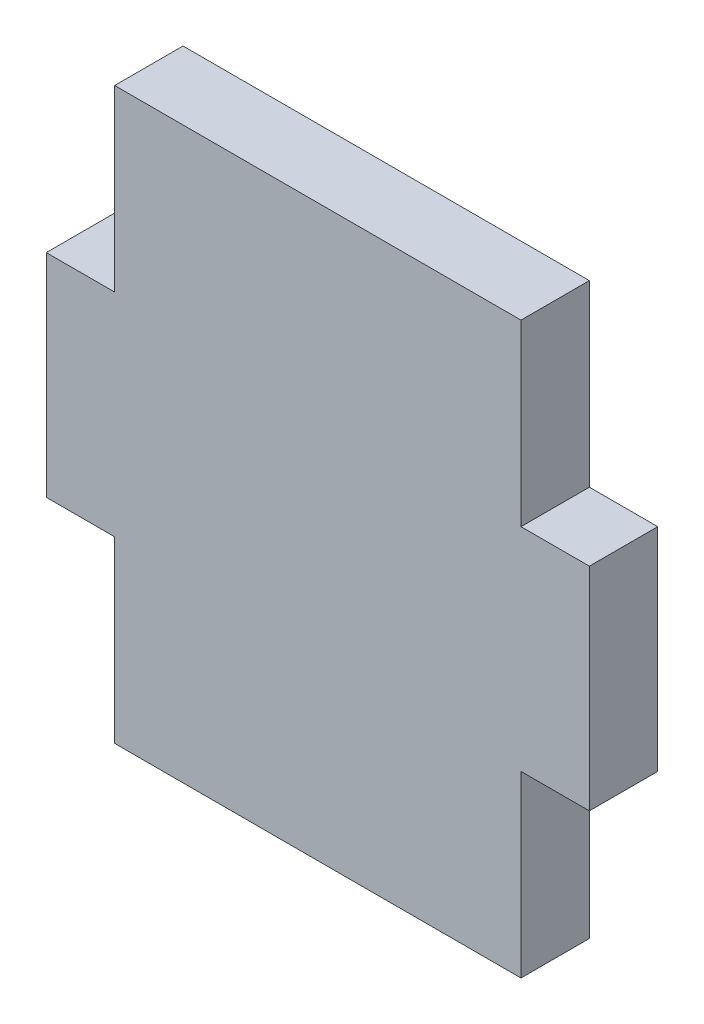
SolidWorks part; units mm, degrees
ref_plane "Front Plane" through (0, 0, 0) normal (0, 0, 1) x (1, 0, 0)
ref_plane "Top Plane" through (0, 0, 0) normal (0, 1, 0) x (1, 0, 0)
ref_plane "Right Plane" through (0, 0, 0) normal (1, 0, 0) x (0, 0, -1)
sketch "Sketch1" plane through (0, 0, 0) normal (0, 0, 1) x (1, 0, 0)
  line L0 (0, -14.224) -> (0, -10.2362)
  line L1 (0, -10.2362) -> (-1.524, -10.2362)
  line L2 (-1.524, -10.2362) -> (-1.524, -5.5118)
  line L3 (-1.524, -5.5118) -> (0, -5.5118)
  line L4 (0, -5.5118) -> (0, -1.524)
  line L5 (0, -1.524) -> (9.0572, -1.524)
  line L6 (9.0572, -1.524) -> (9.0572, -5.5118)
  line L7 (9.0572, -5.5118) -> (10.5812, -5.5118)
  line L8 (10.5812, -5.5118) -> (10.5812, -10.2362)
  line L9 (10.5812, -10.2362) -> (9.0572, -10.2362)
  line L10 (9.0572, -10.2362) -> (9.0572, -14.224)
  line L11 (9.0572, -14.224) -> (0, -14.224)
extrude "Boss-Extrude1" add sketch "Sketch1" along normal blind 1.524
